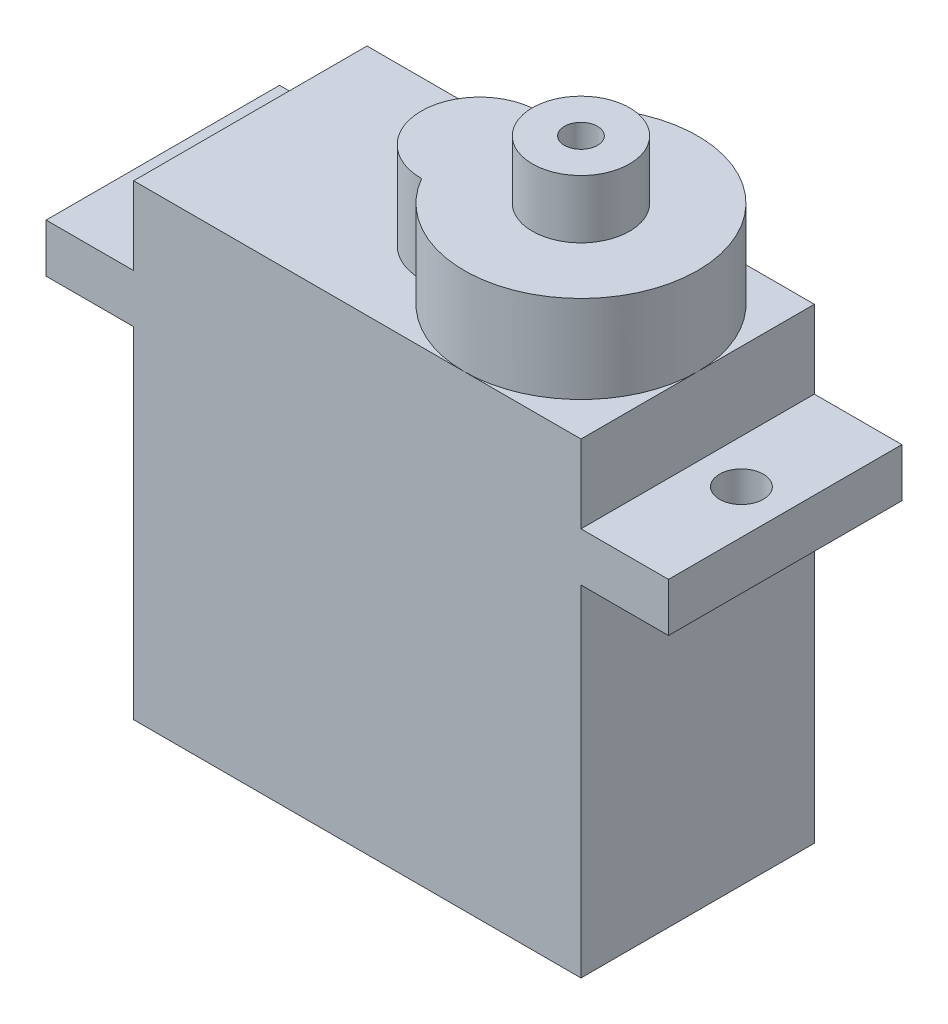
SolidWorks part; units mm, degrees
ref_plane "Front Plane" through (0, 0, 0) normal (0, 0, 1) x (1, 0, 0)
ref_plane "Top Plane" through (0, 0, 0) normal (0, 1, 0) x (1, 0, 0)
ref_plane "Right Plane" through (0, 0, 0) normal (1, 0, 0) x (0, 0, -1)
sketch "Sketch1" plane through (0, 0, 0) normal (0, 1, 0) x (1, 0, 0)
  line L1 (-11.5, 6) -> (11.5, 6)
  line L2 (-11.5, 6) -> (-11.5, -6)
  line L3 (-11.5, -6) -> (11.5, -6)
  line L4 (11.5, 6) -> (11.5, -6)
  line L5 (0, -6) -> (0, 6) construction
  line L6 (-11.5, 0) -> (11.5, 0) construction
  point P0 (0, 0)
  dimension "D1" = 23
  dimension "D2" = 12
extrude "Boss-Extrude1" add sketch "Sketch1" along normal blind 24
sketch "Sketch2" plane through (0, 24, 0) normal (0, 1, 0) x (1, 0, 0)
  line L0 (0.29, 6) -> (0.29, 2.9759) construction
  line L1 (11.5, 6) -> (-11.5, 6) construction
  line L2 (-11.5, -6) -> (11.5, -6) construction
  line L3 (11.5, -6) -> (11.5, 6) construction
  line L4 (0.29, 0) -> (11.5, 0) construction
  line L5 (0.29, -2.9759) -> (0.29, -6) construction
  arc A0 (0.3038, 3) -> (0.3038, -3) centre (0.29, 0) ccw
  arc A1 (0.3038, -3) -> (0.3038, 3) centre (5.5, 0) ccw
  dimension "D2" = 6
  dimension "D1" = 11.21
extrude "Boss-Extrude2" add sketch "Sketch2" along normal blind 4.5
sketch "Sketch3" plane through (0, 28.5, 0) normal (0, 1, 0) x (1, 0, 0)
  circle A0 centre (5.5, 0) radius 2.5
  dimension "D1" = 5
extrude "Boss-Extrude3" add sketch "Sketch3" along normal blind 3
sketch "Sketch4" plane through (0, 31.5, 0) normal (0, 1, 0) x (1, 0, 0)
  circle A0 centre (5.5, 0) radius 0.85
  dimension "D1" = 1.7
extrude "Cut-Extrude1" cut sketch "Sketch4" against normal blind 5
sketch "Sketch5" plane through (0, 24, 0) normal (0, 1, 0) x (1, 0, 0)
  line L0 (-11.5, -6) -> (5.5, -6) construction
  line L1 (-11.5, 6) -> (-16, 6)
  line L2 (-11.5, 6) -> (-11.5, -6)
  line L3 (-11.5, -6) -> (-16, -6)
  line L4 (-16, 6) -> (-16, -6)
  line L5 (-16, 0) -> (-11.5, 0) construction
  line L6 (0, 6) -> (0, -6) construction
  line L7 (5.5, 6) -> (-11.5, 6) construction
  line L8 (16, 0) -> (11.5, 0) construction
  line L9 (16, 6) -> (16, -6)
  line L10 (11.5, -6) -> (16, -6)
  line L11 (11.5, 6) -> (11.5, -6)
  line L12 (11.5, 6) -> (16, 6)
  circle A0 centre (-13.75, 0) radius 1.125
  circle A1 centre (13.75, 0) radius 1.125
  dimension "D2" = 2.25
  dimension "D1" = 4.5
extrude "Boss-Extrude4" add sketch "Sketch5" against normal blind 2.5 from offset 4
